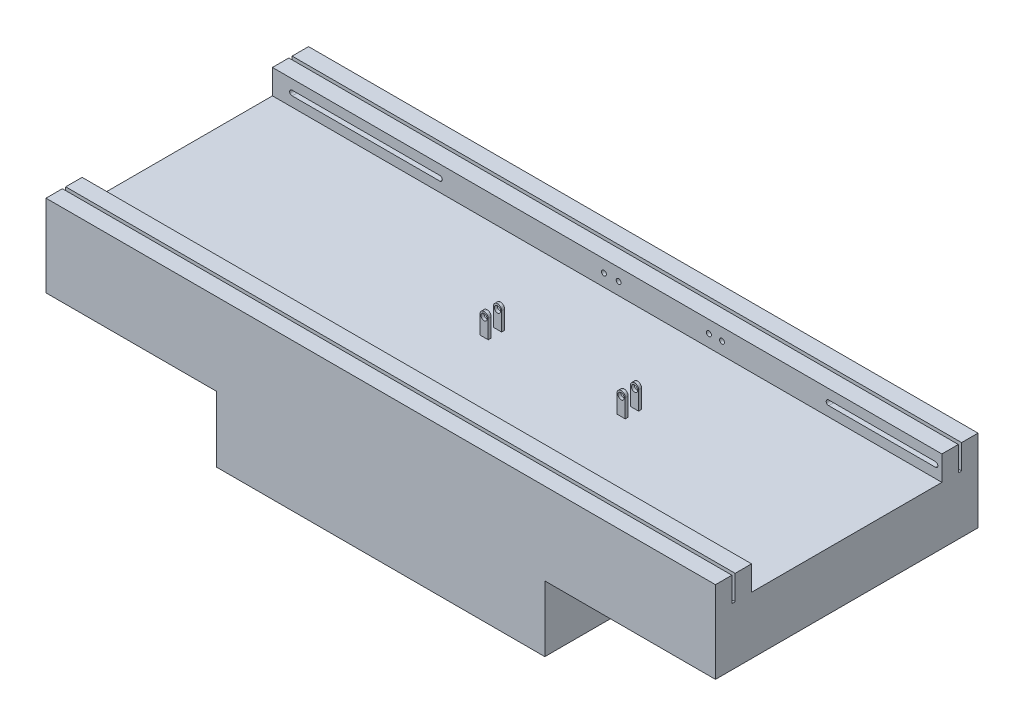
SolidWorks part; units mm, degrees
ref_plane "Front Plane" through (0, 0, 0) normal (0, 0, 1) x (1, 0, 0)
ref_plane "Top Plane" through (0, 0, 0) normal (0, 1, 0) x (1, 0, 0)
ref_plane "Right Plane" through (0, 0, 0) normal (1, 0, 0) x (0, 0, -1)
sketch "Sketch1" plane through (0, 0, 0) normal (0, 0, 1) x (1, 0, 0)
  line L0 (-1435.0087, 0) -> (1435.0087, 0) construction
  line L1 (0, 937.435) -> (0, -937.435) construction
  line L2 (-900, 182.4957) -> (900, 182.4957)
  line L3 (900, 182.4957) -> (900, -67.5043)
  line L4 (900, -67.5043) -> (500, -67.5043)
  line L5 (500, -67.5043) -> (500, -267.5043)
  line L6 (500, -267.5043) -> (-500, -267.5043)
  line L7 (-500, -67.5043) -> (-500, -267.5043)
  line L8 (-900, -67.5043) -> (-500, -67.5043)
  line L9 (-900, 182.4957) -> (-900, -67.5043)
  point P4 (0, 0)
  point P8 (0, 0)
  point P11 (0, 182.4957)
  point P16 (0, -267.5043)
  dimension "D1" = 1800
  dimension "D2" = 400
  dimension "D3" = 250
  dimension "D4" = 200
  dimension "D5" = 267.5043
extrude "Boss-Extrude1" add sketch "Sketch1" along normal blind 800
sketch "Sketch2" plane through (0, -67.5043, 0) normal (0, -1, 0) x (1, 0, 0)
  line L0 (850, 25) -> (550, 25)
  line L1 (550, 25) -> (550, 225)
  line L2 (550, 225) -> (850, 225)
  line L3 (850, 225) -> (850, 25)
  line L4 (500, 0) -> (900, 0) construction
  line L5 (900, 800) -> (900, 0) construction
  line L7 (900, 400) -> (-1097.0273, 400) construction
  line L9 (0, 0) -> (0, 882.015) construction
  line L10 (-550, 225) -> (-850, 225)
  line L11 (-550, 25) -> (-550, 225)
  line L12 (-850, 25) -> (-550, 25)
  line L13 (-850, 225) -> (-850, 25)
  line L14 (-550, 775) -> (-550, 575)
  line L15 (-850, 775) -> (-550, 775)
  line L16 (-850, 575) -> (-850, 775)
  line L17 (-550, 575) -> (-850, 575)
  line L18 (550, 575) -> (850, 575)
  line L19 (550, 775) -> (550, 575)
  line L20 (850, 775) -> (550, 775)
  line L21 (850, 575) -> (850, 775)
  dimension "D1" = 25
  dimension "D2" = 50
  dimension "D3" = 300
  dimension "D4" = 200
extrude "Cut-Extrude1" cut sketch "Sketch2" against normal blind 125
ref_plane "Plane2" through (0, 0, 400) normal (0, 0, -1) x (-1, 0, 0)
sketch "Sketch4" plane through (0, 0, 400) normal (0, 0, -1) x (-1, 0, 0)
  line L0 (-500, -67.5043) -> (-900, -67.5043) construction
  line L1 (0, 485.5822) -> (0, -485.5822) construction
  line L2 (-775, -67.5043) -> (-625, -67.5043)
  line L3 (625, -67.5043) -> (775, -67.5043)
  line L4 (-850, -67.5043) -> (-550, -67.5043) construction
  arc A0 (-625, -67.5043) -> (-775, -67.5043) centre (-700, -67.5043) cw
  arc A1 (625, -67.5043) -> (775, -67.5043) centre (700, -67.5043) ccw
  circle A2 centre (-700, -117.5043) radius 12.5
  circle A3 centre (700, -117.5043) radius 12.5
  point P9 (0, 0)
  dimension "D2" = 50
  dimension "D3" = 25
  dimension "D4" = 75
  dimension "D1" = 150
extrude "Boss-Extrude2" add sketch "Sketch4" against normal blind 100 and the other way blind 100
sketch "Sketch5" plane through (0, 182.4957, 0) normal (0, 1, 0) x (1, 0, 0)
  line L0 (900, -50) -> (900, -750)
  line L1 (900, -750) -> (-900, -750)
  line L2 (-900, -750) -> (-900, -50)
  line L3 (-900, -50) -> (900, -50)
  line L4 (900, 0) -> (-900, 0) construction
  line L5 (900, -800) -> (-900, -800) construction
  line L6 (900, -800) -> (900, 0) construction
  line L7 (-900, -800) -> (-900, 0) construction
  dimension "D1" = 50
  dimension "D2" = 50
  dimension "D3" = 0
  dimension "D4" = 0
extrude "Cut-Extrude2" cut sketch "Sketch5" against normal blind 75
sketch "Sketch8" plane through (0, 0, 0) normal (1, 0, 0) x (0, 0, -1)
  line L0 (-740, 107.4957) -> (-740, 182.4957)
  line L1 (-750, 107.4957) -> (-50, 107.4957) construction
  line L2 (-740, 182.4957) -> (-690, 182.4957)
  line L3 (-690, 182.4957) -> (-690, 107.4957)
  line L4 (-690, 107.4957) -> (-740, 107.4957)
  line L5 (-750, 107.4957) -> (-750, 182.4957) construction
  line L6 (-400, -247.5) -> (-400, 247.5) construction
  line L7 (-60, 107.4957) -> (-60, 182.4957)
  line L8 (-110, 107.4957) -> (-60, 107.4957)
  line L9 (-110, 182.4957) -> (-110, 107.4957)
  line L10 (-60, 182.4957) -> (-110, 182.4957)
  dimension "D1" = 50
  dimension "D2" = 10
  dimension "D3" = 75
extrude "Boss-Extrude3" add sketch "Sketch8" along normal blind 900 and the other way blind 900
sketch "Sketch9" plane through (900, 0, 0) normal (1, 0, 0) x (0, 0, -1)
  line L0 (-800, 182.4957) -> (-750, 182.4957)
  line L1 (-800, 182.4957) -> (-750, 182.4957) construction
  line L2 (-750, 182.4957) -> (-750, 107.4957)
  line L3 (-750, 107.4957) -> (-740, 107.4957)
  line L4 (-740, 107.4957) -> (-740, 182.4957)
  line L5 (-740, 182.4957) -> (-690, 182.4957)
  line L6 (-690, 182.4957) -> (-690, 107.4957)
  line L7 (-690, 107.4957) -> (-690, 182.4957) construction
  line L8 (-690, 107.4957) -> (-110, 107.4957)
  line L12 (0, -67.5043) -> (-800, -67.5043)
  line L13 (-800, -67.5043) -> (-800, 182.4957)
  line L14 (-110, 182.4957) -> (-110, 107.4957)
  line L15 (0, 182.4957) -> (-50, 182.4957)
  line L16 (-50, 182.4957) -> (-50, 107.4957)
  line L17 (0, -67.5043) -> (0, 182.4957)
  line L18 (-60, 182.4957) -> (-110, 182.4957)
  line L19 (-50, 107.4957) -> (-60, 107.4957)
  line L20 (-60, 107.4957) -> (-60, 182.4957)
  dimension "D1" = 580
  dimension "D2" = 10
  dimension "D3" = 50
  dimension "D4" = 50
  dimension "D5" = 75
extrude "Boss-Extrude4" add sketch "Sketch9" along normal blind 120
sketch "Sketch10" plane through (-900, 0, 0) normal (-1, 0, 0) x (0, 0, 1)
  line L0 (800, 182.4957) -> (750, 182.4957)
  line L1 (750, 182.4957) -> (800, 182.4957) construction
  line L2 (750, 182.4957) -> (750, 107.4957)
  line L3 (740, 107.4957) -> (740, 182.4957)
  line L4 (740, 182.4957) -> (690, 182.4957)
  line L5 (690, 182.4957) -> (690, 107.4957)
  line L6 (690, 107.4957) -> (110, 107.4957)
  line L7 (110, 107.4957) -> (110, 182.4957)
  line L8 (110, 182.4957) -> (60, 182.4957)
  line L9 (60, 182.4957) -> (60, 107.4957)
  line L10 (60, 107.4957) -> (50, 107.4957)
  line L11 (50, 107.4957) -> (50, 182.4957)
  line L12 (0, 182.4957) -> (50, 182.4957) construction
  line L13 (50, 182.4957) -> (50, 107.4957) construction
  line L14 (50, 182.4957) -> (0, 182.4957)
  line L15 (0, 182.4957) -> (0, -67.5043)
  line L16 (0, -67.5043) -> (800, -67.5043)
  line L17 (800, -67.5043) -> (800, 182.4957)
  line L18 (750, 107.4957) -> (740, 107.4957)
extrude "Boss-Extrude5" add sketch "Sketch10" along normal blind 120
sketch "Sketch7" plane through (0, 0, 750) normal (0, 0, -1) x (-1, 0, 0)
  line L0 (0, 800.1675) -> (0, -800.1675) construction
  line L1 (-1193.3565, 144.9957) -> (1193.3565, 144.9957) construction
  line L2 (-1020, 182.4957) -> (1020, 182.4957) construction
  line L3 (1020, 57.4957) -> (1020, 372.8849) construction
  line L4 (1020, -67.5043) -> (1020, 182.4957) construction
  line L7 (960, 144.9957) -> (510, 144.9957) construction
  line L10 (960, 137.4957) -> (510, 137.4957)
  line L13 (-1020, 107.4957) -> (-1020, 182.4957) construction
  line L16 (-1000, 144.9957) -> (-675, 144.9957) construction
  line L17 (-1000, 152.4957) -> (-675, 152.4957)
  line L18 (-1000, 137.4957) -> (-675, 137.4957)
  line L19 (960, 152.4957) -> (510, 152.4957)
  circle A7 centre (-35, 144.9957) radius 7.5
  circle A9 centre (-350, 144.9957) radius 7.5
  arc A19 (-1000, 152.4957) -> (-1000, 137.4957) centre (-1000, 144.9957) ccw
  arc A20 (-675, 137.4957) -> (-675, 152.4957) centre (-675, 144.9957) ccw
  circle A21 centre (-310, 144.9957) radius 7.5
  arc A22 (960, 137.4957) -> (960, 152.4957) centre (960, 144.9957) ccw
  arc A23 (510, 152.4957) -> (510, 137.4957) centre (510, 144.9957) ccw
  circle A24 centre (10, 144.9957) radius 7.5
  point P4 (0, 0)
  point P8 (0, 144.9957)
  point P15 (735, 144.9957)
  point P29 (-837.5, 144.9957)
  dimension "D3" = 10
  dimension "D4" = 7.5
  dimension "D5" = 450
  dimension "D6" = 500
  dimension "D7" = 15
  dimension "D13" = 40
  dimension "D14" = 15
  dimension "D16" = 15
  dimension "D17" = 15
  dimension "D18" = 275
  dimension "D19" = 20
  dimension "D20" = 325
  dimension "D22" = 7.5
  dimension "D26" = 325
  dimension "D1" = 37.5
extrude "Cut-Extrude4" cut sketch "Sketch7" against normal blind 40 and the other way blind 740
sketch "Sketch12" plane through (0, 0, 400) normal (0, 0, -1) x (-1, 0, 0)
  line L0 (1020, 182.4957) -> (1020, 107.4957) construction
  line L1 (1020, -67.5043) -> (1020, 182.4957) construction
  line L2 (1020, 107.4957) -> (-1910.404, 107.4957) construction
  line L8 (72.5, 107.4957) -> (72.5, 163.5957)
  line L9 (60.1, 175.9957) -> (59.9, 175.9957)
  line L10 (47.5, 163.5957) -> (47.5, 107.4957)
  line L11 (47.5, 107.4957) -> (72.5, 107.4957)
  line L12 (-345, 107.4957) -> (-345, 163.5957)
  line L13 (-357.4, 175.9957) -> (-357.6, 175.9957)
  line L14 (-370, 163.5957) -> (-370, 107.4957)
  line L15 (-370, 107.4957) -> (-345, 107.4957)
  line L16 (-1020, 182.4957) -> (-1020, -67.5043) construction
  circle A3 centre (60, 160.9957) radius 9.525
  arc A4 (72.5, 163.5957) -> (60.1, 175.9957) centre (60.1, 163.5957) ccw
  arc A5 (59.9, 175.9957) -> (47.5, 163.5957) centre (59.9, 163.5957) ccw
  circle A6 centre (-357.5, 160.9957) radius 9.525
  arc A7 (-357.6, 175.9957) -> (-370, 163.5957) centre (-357.6, 163.5957) ccw
  arc A8 (-345, 163.5957) -> (-357.4, 175.9957) centre (-357.4, 163.5957) ccw
  point P14 (72.5, 175.9957)
  point P17 (47.5, 175.9957)
  point P27 (-370, 175.9957)
  point P30 (-345, 175.9957)
  dimension "D5" = 68.5
  dimension "D6" = 15
  dimension "D4" = 12.5
  dimension "D2" = 19.05
  dimension "D3" = 25
  dimension "D7" = 12.4
  dimension "D8" = 960
  dimension "D11" = 12.5
  dimension "D12" = 19.05
  dimension "D13" = 12.4
  dimension "D14" = 15
  dimension "D1" = 75
  dimension "D9" = 25
  dimension "D10" = 68.5
  dimension "D15" = 650
extrude "Boss-Extrude6" add sketch "Sketch12" along normal blind 25 and the other way blind 25
sketch "Sketch13" plane through (-72.5, 0, 0) normal (-1, 0, 0) x (0, 0, 1)
  line L0 (415.875, 107.4957) -> (415.875, 175.9957)
  line L1 (425, 107.4957) -> (375, 107.4957) construction
  line L4 (384.125, 175.9957) -> (384.125, 107.4957)
  line L5 (384.125, 107.4957) -> (415.875, 107.4957)
  line L6 (425, 163.5957) -> (425, 107.4957) construction
  line L7 (425, 175.9957) -> (375, 175.9957) construction
  line L8 (415.875, 175.9957) -> (384.125, 175.9957)
  dimension "D1" = 31.75
  dimension "D2" = 9.125
extrude "Cut-Extrude5" cut sketch "Sketch13" against normal through all
